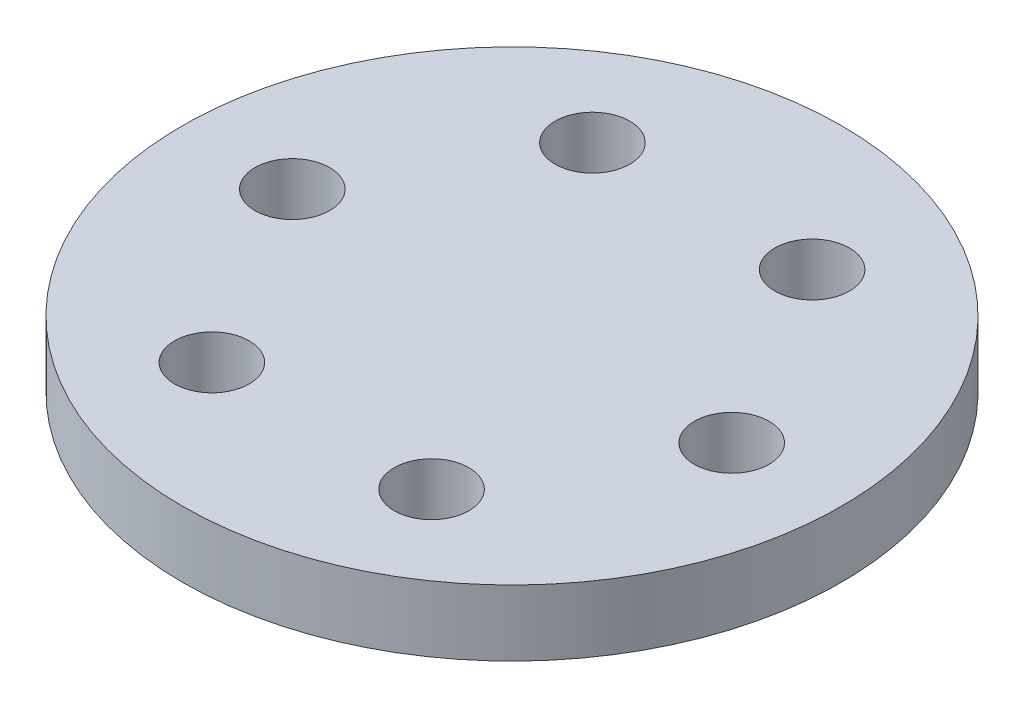
SolidWorks part; units mm, degrees
ref_plane "Front Plane" through (0, 0, 0) normal (0, 0, 1) x (1, 0, 0)
ref_plane "Top Plane" through (0, 0, 0) normal (0, 1, 0) x (1, 0, 0)
ref_plane "Right Plane" through (0, 0, 0) normal (1, 0, 0) x (0, 0, -1)
sketch "Sketch1" plane through (0, 0, 0) normal (0, 1, 0) x (1, 0, 0)
  line L0 (0, 0) -> (10, 0) construction
  circle A0 centre (0, 0) radius 15
  circle A1 centre (10, 0) radius 1.7
  circle A2 centre (5, -8.6603) radius 1.7
  circle A3 centre (-5, -8.6603) radius 1.7
  circle A4 centre (-10, 0) radius 1.7
  circle A5 centre (-5, 8.6603) radius 1.7
  circle A6 centre (5, 8.6603) radius 1.7
  point P5 (0, 0)
  point P6 (0, 0)
  point P17 (0, 0)
  point P18 (-10, 0)
  dimension "D1" = 30
  dimension "D2" = 10
  dimension "D3" = 3.4
  dimension "D4" = 6
extrude "Boss-Extrude1" add sketch "Sketch1" along normal blind 3
